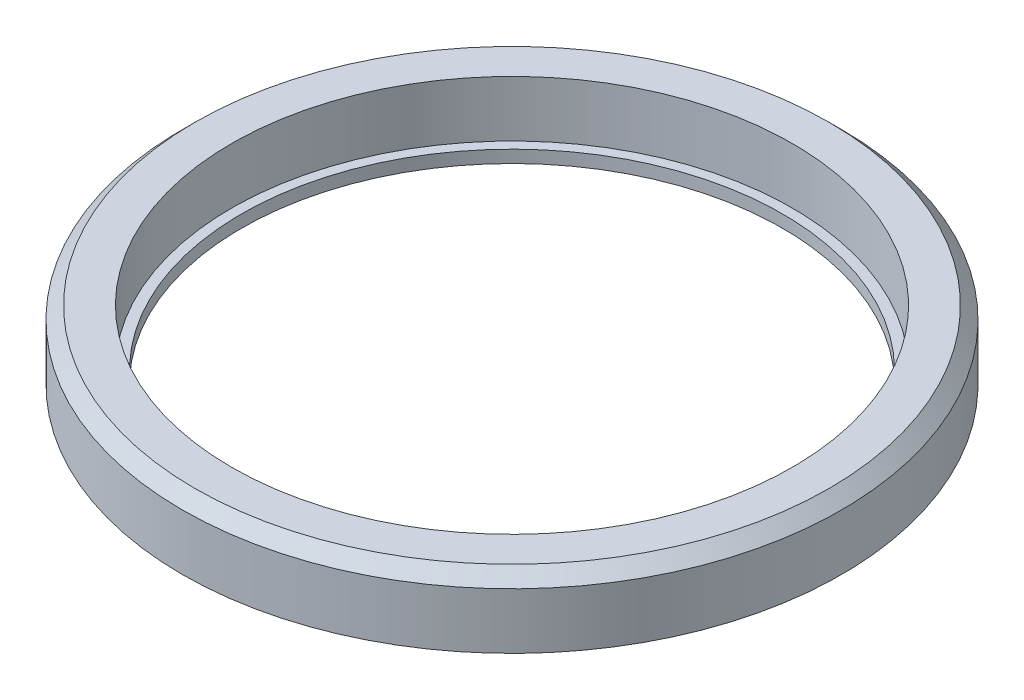
SolidWorks part; units mm, degrees
ref_plane "Front Plane" through (0, 0, 0) normal (0, 0, 1) x (1, 0, 0)
ref_plane "Top Plane" through (0, 0, 0) normal (0, 1, 0) x (1, 0, 0)
ref_plane "Right Plane" through (0, 0, 0) normal (1, 0, 0) x (0, 0, -1)
sketch "Sketch1" plane through (0, 0, 0) normal (0, 1, 0) x (1, 0, 0)
  circle A0 centre (0, 0) radius 53
  circle A1 centre (0, 0) radius 43.5
  dimension "D1" = 106
  dimension "D2" = 87
extrude "Boss-Extrude1" add sketch "Sketch1" along normal blind 11
sketch "Sketch2" plane through (0, 11, 0) normal (0, 1, 0) x (1, 0, 0)
  circle A0 centre (0, 0) radius 45.1
  dimension "D1" = 90.2
extrude "Cut-Extrude1" cut sketch "Sketch2" against normal blind 9
chamfer "Chamfer1" distance 2 angle 45 1 edges at (0, 11, 53)
